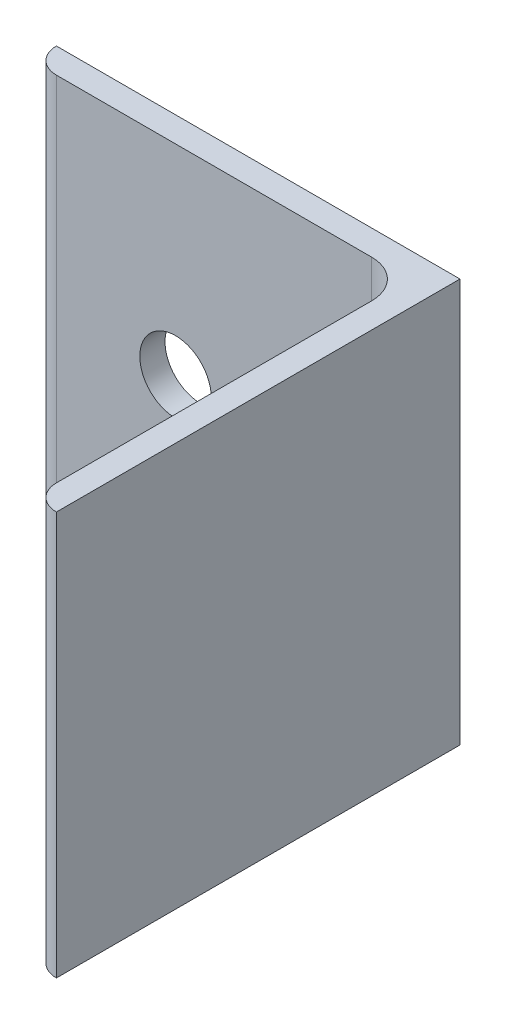
SolidWorks part; units mm, degrees
ref_plane "Alzado" through (0, 0, 0) normal (0, 0, 1) x (1, 0, 0)
ref_plane "Planta" through (0, 0, 0) normal (0, 1, 0) x (1, 0, 0)
ref_plane "Vista lateral" through (0, 0, 0) normal (1, 0, 0) x (0, 0, -1)
sketch "Croquis1" plane through (0, 0, 0) normal (0, 0, 1) x (1, 0, 0)
  line L0 (0, 0) -> (0, 50.8)
  dimension "D1" = 50.8
other "Hierro angular 2 X 2 X 0.125(1)"
ref_plane "Plano1" through (0, 0, 0) normal (0, 1, 0) x (-1, 0, 0)
sketch "Sketch1" plane through (0, 0, 0) normal (0, 1, 0) x (-1, 0, 0)
  line L0 (0, 0) -> (0, 50.8)
  line L1 (0, 50.8) -> (0.0051, 50.8)
  line L2 (3.175, 47.6301) -> (3.175, 7.9375)
  line L3 (7.9375, 3.175) -> (47.6301, 3.175)
  line L4 (50.8, 0.0051) -> (50.8, 0)
  line L5 (50.8, 0) -> (0, 0)
  arc A0 (50.8, 0.0051) -> (47.6301, 3.175) centre (47.6301, 0.0051) ccw
  arc A1 (0.0051, 50.8) -> (3.175, 47.6301) centre (0.0051, 47.6301) cw
  arc A2 (7.9375, 3.175) -> (3.175, 7.9375) centre (7.9375, 7.9375) cw
  point P10 (25.4, 0)
  point P14 (0, 25.4)
  point P15 (3.175, 25.4)
  point P16 (25.4, 3.175)
  point P17 (3.175, 50.8)
  point P18 (50.8, 3.175)
  point P19 (0, 0)
  dimension "D2" = 0.0051
  dimension "Radius_1" = 4.7625
  dimension "D1" = 3.175
  dimension "H_leg" = 50.8
sketch "Croquis3" plane through (0, 0, 3.175) normal (0, 0, 1) x (1, 0, 0)
  line L0 (-7.9375, 0) -> (-47.6301, 0) construction
  line L1 (-47.6301, 0) -> (-27.7838, 0) construction
  line L2 (-32.6301, 20.9) -> (-32.6301, 25.4) construction
  line L4 (-32.6301, 29.9) -> (-32.6301, 25.4) construction
  line L5 (-32.6301, 25.4) -> (-47.6301, 25.4) construction
  line L6 (-47.6301, 50.8) -> (-47.6301, 0) construction
  circle A0 centre (-32.6301, 25.4) radius 4.5
  dimension "D1" = 9
  dimension "D2" = 15
extrude "Cortar-Extruir1" cut sketch "Croquis3" against normal blind 10
